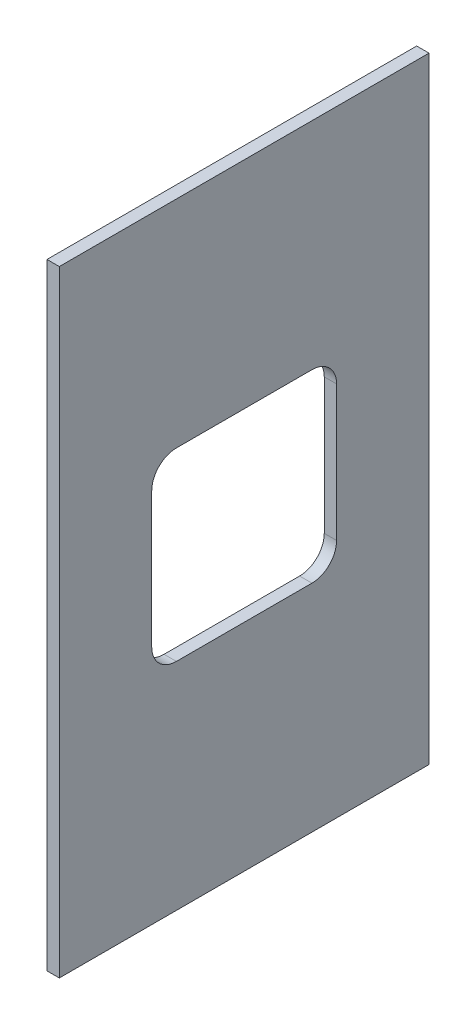
SolidWorks part; units mm, degrees
material "hw11"
ref_plane "Front Plane" through (0, 0, 0) normal (1, 0, 0) x (0, 1, 0)
ref_plane "Top Plane" through (0, 0, 0) normal (0, 0, 1) x (0, 1, 0)
ref_plane "Right Plane" through (0, 0, 0) normal (0, 1, 0) x (-1, 0, 0)
sketch "Sketch1" plane through (0, 0, 0) normal (1, 0, 0) x (0, 1, 0)
  line L1 (0, 0) -> (500, 0)
  line L2 (0, 0) -> (0, 300)
  line L3 (0, 300) -> (500, 300)
  line L4 (500, 0) -> (500, 300)
  line L5 (195, 75) -> (305, 75)
  line L6 (175, 95) -> (175, 205)
  line L7 (195, 225) -> (305, 225)
  line L8 (325, 95) -> (325, 205)
  arc A1 (305, 75) -> (325, 95) centre (305, 95) ccw
  arc A2 (305, 225) -> (325, 205) centre (305, 205) cw
  arc A3 (175, 205) -> (195, 225) centre (195, 205) cw
  arc A4 (195, 75) -> (175, 95) centre (195, 95) cw
  point P7 (250, 0)
  point P8 (250, 75)
  point P9 (0, 150)
  point P12 (175, 150)
  point P15 (325, 75)
  point P22 (175, 75)
  dimension "D3" = 150
  dimension "D4" = 20
  dimension "D1" = 500
  dimension "D2" = 300
extrude "Boss-Extrude1" add sketch "Sketch1" along normal blind 10
